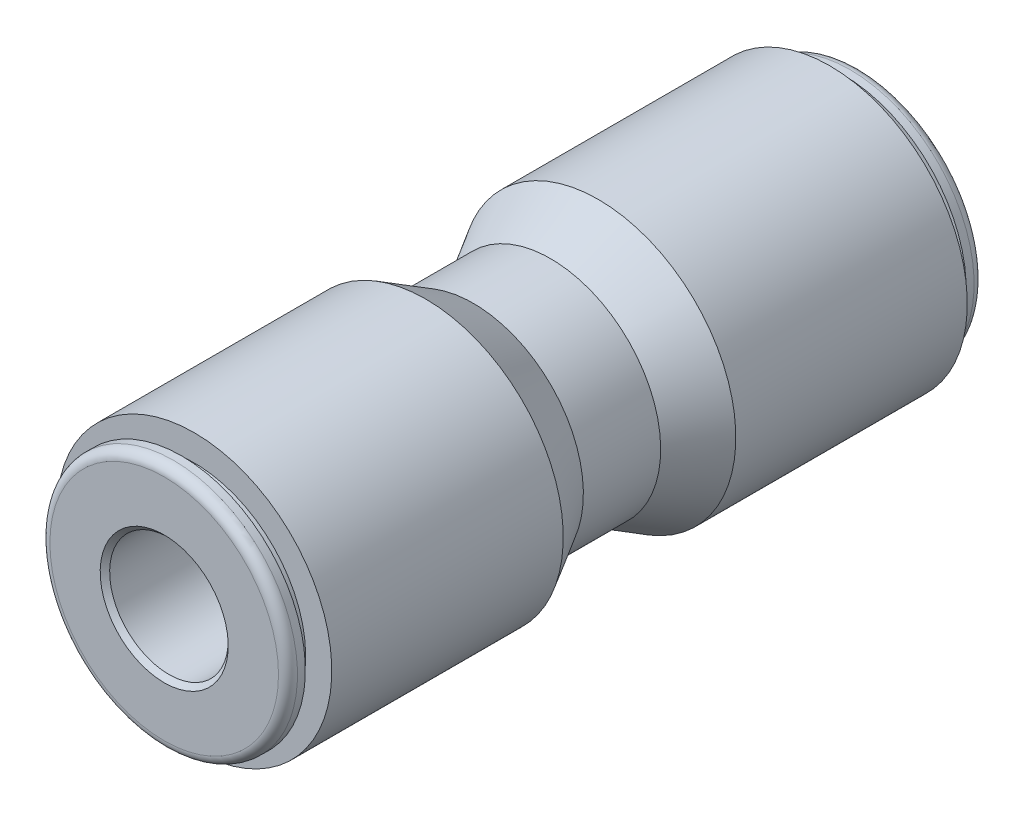
SolidWorks part; units mm, degrees
ref_plane "Front Plane" through (0, 0, 0) normal (0, 0, 1) x (1, 0, 0)
ref_plane "Top Plane" through (0, 0, 0) normal (0, 1, 0) x (1, 0, 0)
ref_plane "Right Plane" through (0, 0, 0) normal (1, 0, 0) x (0, 0, -1)
sketch "Sketch1" plane through (0, 0, 0) normal (1, 0, 0) x (0, 0, -1)
  line L0 (26.543, 9.9441) -> (27.178, 9.9441)
  line L1 (6.9319, 11.049) -> (25.527, 11.049)
  line L2 (-3.1044, 8.8392) -> (-6.9319, 11.049)
  line L3 (0.254, 6.35) -> (27.559, 6.35)
  line L4 (27.94, 9.1821) -> (27.94, 6.731)
  line L5 (0.254, 6.35) -> (0.254, 3.175)
  line L6 (25.527, 11.049) -> (25.527, 8.9497)
  line L7 (25.527, 8.9497) -> (26.543, 8.9497)
  line L8 (26.543, 9.9441) -> (26.543, 8.9497)
  line L9 (0.254, 3.175) -> (0, 3.175) construction
  line L10 (0, 0) -> (27.94, 0) construction
  line L11 (-6.9319, 11.049) -> (-25.527, 11.049)
  line L12 (27.559, 6.35) -> (27.94, 6.731)
  line L13 (0, 0) -> (0, 3.175) construction
  line L14 (-3.1044, 8.8392) -> (3.1044, 8.8392)
  line L15 (3.1044, 8.8392) -> (6.9319, 11.049)
  line L16 (-25.527, 11.049) -> (-25.527, 8.9497)
  line L17 (-25.527, 8.9497) -> (-26.543, 8.9497)
  line L18 (-26.543, 9.9441) -> (-26.543, 8.9497)
  line L19 (-26.543, 9.9441) -> (-27.178, 9.9441)
  line L20 (-27.94, 9.1821) -> (-27.94, 5.1435)
  line L21 (0.254, 3.175) -> (-7.112, 3.175)
  line L22 (-7.112, 3.175) -> (-7.112, 4.7625)
  line L23 (-7.112, 4.7625) -> (-27.559, 4.7625)
  line L24 (-27.559, 4.7625) -> (-27.94, 5.1435)
  arc A0 (27.178, 9.9441) -> (27.94, 9.1821) centre (27.178, 9.1821) cw
  arc A1 (-27.178, 9.9441) -> (-27.94, 9.1821) centre (-27.178, 9.1821) ccw
  point P1 (27.94, 6.35)
  point P20 (27.94, 9.9441)
  dimension "D4" = 0.762
  dimension "D1" = 1.397
  dimension "D2" = 1.016
  dimension "D3" = 17.8994
  dimension "D6" = 19.8882
  dimension "D9" = 30
  dimension "D10" = 17.6784
  dimension "D5" = 24.8356
revolve "Revolve1" add sketch "Sketch1" angle 360 about L10
sketch "SketchZ" plane through (0, 0, 0) normal (1, 0, 0) x (0, 0, -1)
  line L0 (0.254, 6.35) -> (27.94, 6.35)
  line L1 (27.94, -9.1821) -> (27.94, 9.1821) construction
  line L2 (0.254, -6.35) -> (27.94, -6.35)
  line L3 (-7.112, -4.7625) -> (-27.94, -4.7625)
  line L5 (-7.112, 4.7625) -> (-27.94, 4.7625)
  line L6 (0.254, 6.35) -> (0.254, 3.175)
  line L7 (0.254, 3.175) -> (-7.112, 3.175)
  line L8 (-7.112, 3.175) -> (-7.112, 4.7625)
  line L9 (0.254, -6.35) -> (0.254, -3.175)
  line L10 (0.254, -3.175) -> (-7.112, -3.175)
  line L11 (-7.112, -3.175) -> (-7.112, -4.7625)
  line L12 (0.254, 3.175) -> (-7.112, 3.175) construction
  line L13 (0.254, -6.35) -> (0.254, 6.35) construction
  line L14 (-7.112, -3.175) -> (0.254, -3.175) construction
  line L15 (-27.94, 9.1821) -> (-27.94, -9.1821) construction
equation "\"D3@Sketch1\" = \"D6@Sketch1\"*.9"
equation "\"D6@Sketch1\" = \"G@Sketch1\"*.9"
equation "\"D10@Sketch1\" = \"G@Sketch1\"*.8"
equation "\"D5@Sketch1\" = \"L@Sketch1\"/2.25"
